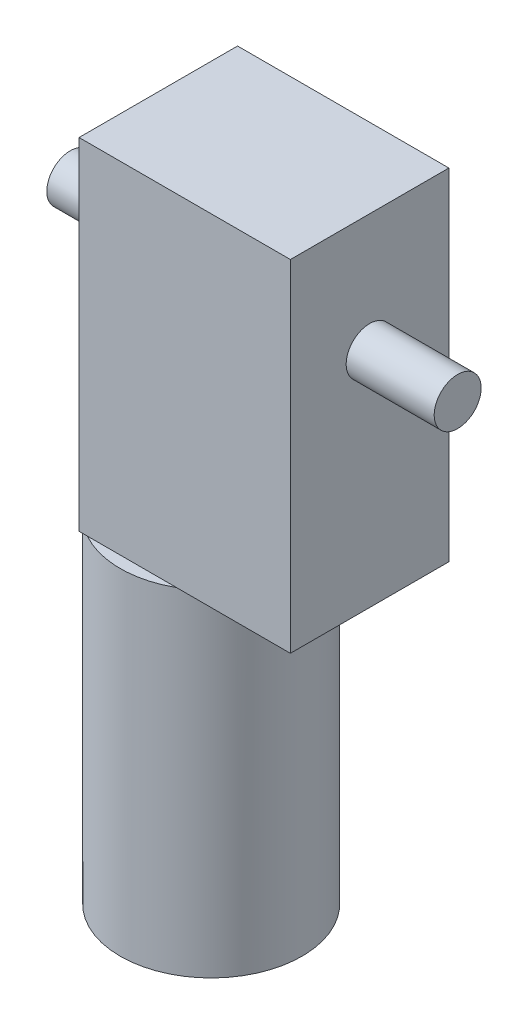
SolidWorks part; units mm, degrees
material "Alloy Steel"
ref_plane "Front Plane" through (0, 0, 0) normal (0, 0, 1) x (1, 0, 0)
ref_plane "Top Plane" through (0, 0, 0) normal (0, 1, 0) x (1, 0, 0)
ref_plane "Right Plane" through (0, 0, 0) normal (1, 0, 0) x (0, 0, -1)
sketch "Sketch2" plane through (0, 0, 0) normal (0, 1, 0) x (1, 0, 0)
  circle A0 centre (0, 0) radius 15.494
  dimension "D1" = 30.988
extrude "Boss-Extrude1" add sketch "Sketch2" along normal blind 57.2 contours A0
sketch "Sketch3" plane through (0, 57.2, 0) normal (0, 1, 0) x (1, 0, 0)
  line L0 (0, 15.494) -> (0, -15.494) construction
  line L1 (-9, 13.5) -> (27, 13.5)
  line L2 (-9, 13.5) -> (-9, -13.5)
  line L3 (-9, -13.5) -> (27, -13.5)
  line L4 (27, 13.5) -> (27, -13.5)
  line L5 (9, 13.5) -> (9, -13.5) construction
  circle A0 centre (0, 0) radius 15.494 construction
  point P4 (9, 13.5)
  dimension "D1" = 27
  dimension "D2" = 36
  dimension "D3" = 9
extrude "Boss-Extrude2" add sketch "Sketch3" along normal blind 58.1
sketch "Sketch4" plane through (27, 0, 0) normal (1, 0, 0) x (0, 0, -1)
  line L1 (-13.5, 57.2) -> (13.5, 57.2) construction
  circle A0 centre (0, 95.1) radius 4
  dimension "D1" = 37.9
  dimension "D2" = 8
extrude "Boss-Extrude3" add sketch "Sketch4" along normal blind 15 and the other way blind 51
